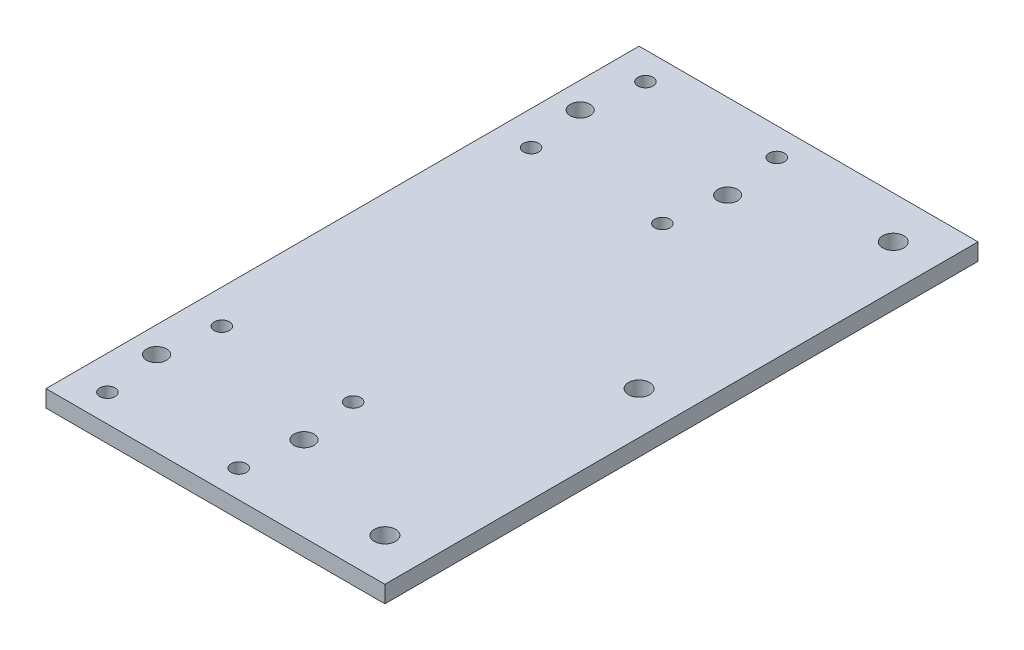
SolidWorks part; units mm, degrees
ref_plane "前视基准面" through (0, 0, 0) normal (0, 0, 1) x (1, 0, 0)
ref_plane "上视基准面" through (0, 0, 0) normal (0, 1, 0) x (1, 0, 0)
ref_plane "右视基准面" through (0, 0, 0) normal (1, 0, 0) x (0, 0, -1)
other "Configuration Table"
sketch "草图2" plane through (0, 0, 0) normal (0, 1, 0) x (1, 0, 0)
  line L0 (0, 70) -> (0, -70)
  line L1 (-80, -70) -> (80, -70)
  line L2 (-80, -70) -> (-80, 70)
  line L3 (-80, 70) -> (80, 70)
  line L4 (80, -70) -> (80, 70)
  line L5 (-80, -70) -> (80, 70) construction
  line L6 (-80, 70) -> (80, -70) construction
  point P0 (0, 0)
  dimension "D1" = 140
  dimension "D2" = 160
extrude "凸台-拉伸1" add sketch "草图2" along normal blind 4 contours L3 L2 L1 L0
ref_plane "基准面1" through (0, 4, 0) normal (0, 1, 0) x (1, 0, 0)
sketch "草图3" plane through (0, 4, 0) normal (0, 1, 0) x (1, 0, 0)
  line L0 (-1080, 50) -> (48920, 50) construction
  line L1 (-80, 70) -> (-33, 70)
  line L2 (-80, 70) -> (-80, 30)
  line L3 (-80, 30) -> (-33, 30)
  line L4 (-33, 70) -> (-33, 30)
  line L5 (-80, -70) -> (-33, -70)
  line L6 (-80, -70) -> (-80, -30)
  line L7 (-80, -30) -> (-33, -30)
  line L8 (-33, -70) -> (-33, -30)
  line L9 (-56.5, 110.6134) -> (-56.5, 29.3866) construction
  line L10 (-80, 0) -> (49920, 0) construction
  line L11 (-80, -70) -> (-80, 70) construction
  line L12 (0, 70) -> (0, -70) construction
  line L13 (-80, 70) -> (0, 70) construction
  line L14 (0, 70) -> (-10, 70)
  line L15 (0, 70) -> (0, 60)
  line L16 (0, 60) -> (-10, 60)
  line L17 (-10, 70) -> (-10, 60)
  circle A0 centre (-72, 63.5) radius 1.8
  circle A1 centre (-41, 63.5) radius 1.8
  circle A2 centre (-41, 36.5) radius 1.8
  circle A3 centre (-72, 36.5) radius 1.8
  circle A4 centre (-41, -63.5) radius 1.8
  circle A5 centre (-41, -36.5) radius 1.8
  circle A6 centre (-72, -36.5) radius 1.8
  circle A7 centre (-72, -63.5) radius 1.8
  circle A8 centre (-73.9, 50) radius 2.35
  circle A9 centre (-73.9, -50) radius 2.35
  circle A10 centre (-39.1, -50) radius 2.35
  circle A11 centre (-39.1, 50) radius 2.35
  circle A12 centre (-10, 60) radius 2.5
  circle A13 centre (-10, 0) radius 2.5
  circle A14 centre (-10, -60) radius 2.5
  point P13 (-80, 50)
  point P18 (-56.5, 70)
  point P28 (-80, 0)
  point P31 (0, 0)
  point P55 (0, 0)
  dimension "D5" = 3.6
  dimension "D8" = 4.7
  dimension "D10" = 10
  dimension "D12" = 5
  dimension "D1" = 40
  dimension "D2" = 40
  dimension "D3" = 47
  dimension "D4" = 47
  dimension "D6" = 8
  dimension "D7" = 6.5
  dimension "D9" = 6.1
  dimension "D11" = 10
  dimension "D13" = 3
extrude "切除-拉伸3" cut sketch "草图3" against normal blind 4 contours A0 | A8 | A3 | A2 | A11 | A1 | L16 A12 L17 | L17 A12 L16 | A9 | A6 | A7 | A4 | A10 | A5 | A14 | A13
